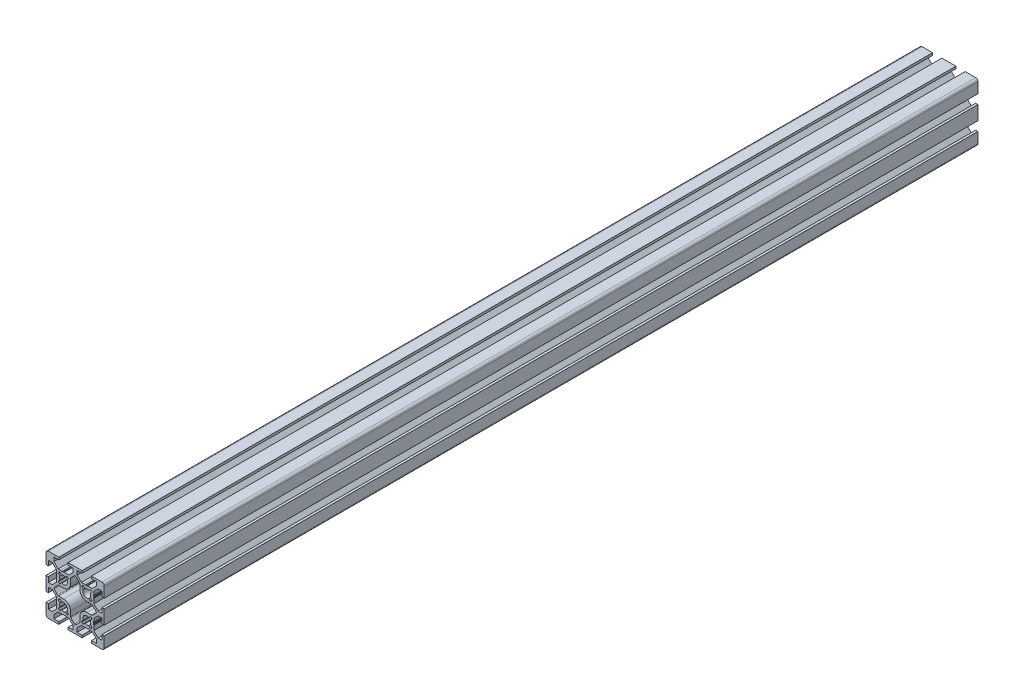
SolidWorks part; units mm, degrees
ref_plane "Front Plane" through (0, 0, 0) normal (0, 0, 1) x (1, 0, 0)
ref_plane "Top Plane" through (0, 0, 0) normal (0, 1, 0) x (1, 0, 0)
ref_plane "Right Plane" through (0, 0, 0) normal (1, 0, 0) x (0, 0, -1)
ref_plane "Plane1" through (0, 0, 0) normal (0, 0, 1) x (1, 0, 0)
sketch "Sketch1" plane through (0, 0, 0) normal (0, 0, 1) x (1, 0, 0)
  line L0 (-25, 23) -> (-25, 14)
  line L1 (-25, 14) -> (-23, 14)
  line L2 (-23, 14) -> (-23, 18.25)
  line L3 (-23, 18.25) -> (-19.6642, 18.25)
  line L4 (-19.6642, 18.25) -> (-16, 14.5858)
  line L5 (-16, 14.5858) -> (-16, 10.6536)
  line L6 (-15.933, 10.4036) -> (-15.7, 10)
  line L7 (-15.7, 10) -> (-15.933, 9.5964)
  line L8 (-15.933, 9.0964) -> (-15.751, 8.7811)
  line L9 (-15.751, 8.7811) -> (-16, 7.5)
  line L10 (-16, 7.5) -> (-16, 5.4142)
  line L11 (-16, 5.4142) -> (-19.6642, 1.75)
  line L12 (-19.6642, 1.75) -> (-23, 1.75)
  line L13 (-23, 1.75) -> (-23, 6)
  line L14 (-23, 6) -> (-25, 6)
  line L15 (-25, 6) -> (-25, -6)
  line L16 (-25, -6) -> (-23, -6)
  line L17 (-23, -6) -> (-23, -1.75)
  line L18 (-23, -1.75) -> (-19.6642, -1.75)
  line L19 (-19.6642, -1.75) -> (-16, -5.4142)
  line L20 (-16, -5.4142) -> (-16, -9.3464)
  line L21 (-15.933, -9.5964) -> (-15.7, -10)
  line L22 (-15.7, -10) -> (-15.933, -10.4036)
  line L23 (-15.933, -10.9036) -> (-15.751, -11.2189)
  line L24 (-15.751, -11.2189) -> (-16, -12.5)
  line L25 (-16, -12.5) -> (-16, -14.5858)
  line L26 (-16, -14.5858) -> (-19.6642, -18.25)
  line L27 (-19.6642, -18.25) -> (-23, -18.25)
  line L28 (-23, -18.25) -> (-23, -14)
  line L29 (-23, -14) -> (-25, -14)
  line L30 (-25, -14) -> (-25, -23)
  line L31 (-23, -25) -> (-14, -25)
  line L32 (-14, -25) -> (-14, -23)
  line L33 (-14, -23) -> (-18.25, -23)
  line L34 (-18.25, -23) -> (-18.25, -19.6642)
  line L35 (-18.25, -19.6642) -> (-14.5858, -16)
  line L36 (-14.5858, -16) -> (-10.6536, -16)
  line L37 (-10.4036, -15.933) -> (-10, -15.7)
  line L38 (-10, -15.7) -> (-9.5964, -15.933)
  line L39 (-9.0964, -15.933) -> (-8.7811, -15.751)
  line L40 (-8.7811, -15.751) -> (-7.5, -16)
  line L41 (-7.5, -16) -> (-5.4142, -16)
  line L42 (-5.4142, -16) -> (-1.75, -19.6642)
  line L43 (-1.75, -19.6642) -> (-1.75, -23)
  line L44 (-1.75, -23) -> (-6, -23)
  line L45 (-6, -23) -> (-6, -25)
  line L46 (-6, -25) -> (6, -25)
  line L47 (6, -25) -> (6, -23)
  line L48 (6, -23) -> (1.75, -23)
  line L49 (1.75, -23) -> (1.75, -19.6642)
  line L50 (1.75, -19.6642) -> (5.4142, -16)
  line L51 (5.4142, -16) -> (9.3464, -16)
  line L52 (9.5964, -15.933) -> (10, -15.7)
  line L53 (10, -15.7) -> (10.4036, -15.933)
  line L54 (10.9036, -15.933) -> (11.2189, -15.751)
  line L55 (11.2189, -15.751) -> (12.5, -16)
  line L56 (12.5, -16) -> (14.5858, -16)
  line L57 (14.5858, -16) -> (18.25, -19.6642)
  line L58 (18.25, -19.6642) -> (18.25, -23)
  line L59 (18.25, -23) -> (14, -23)
  line L60 (14, -23) -> (14, -25)
  line L61 (14, -25) -> (23, -25)
  line L62 (25, -23) -> (25, -14)
  line L63 (25, -14) -> (23, -14)
  line L64 (23, -14) -> (23, -18.25)
  line L65 (23, -18.25) -> (19.6642, -18.25)
  line L66 (19.6642, -18.25) -> (16, -14.5858)
  line L67 (16, -14.5858) -> (16, -10.6536)
  line L68 (15.933, -10.4036) -> (15.7, -10)
  line L69 (15.7, -10) -> (15.933, -9.5964)
  line L70 (15.933, -9.0964) -> (15.751, -8.7811)
  line L71 (15.751, -8.7811) -> (16, -7.5)
  line L72 (16, -7.5) -> (16, -5.4142)
  line L73 (16, -5.4142) -> (19.6642, -1.75)
  line L74 (19.6642, -1.75) -> (23, -1.75)
  line L75 (23, -1.75) -> (23, -6)
  line L76 (23, -6) -> (25, -6)
  line L77 (25, -6) -> (25, 6)
  line L78 (25, 6) -> (23, 6)
  line L79 (23, 6) -> (23, 1.75)
  line L80 (23, 1.75) -> (19.6642, 1.75)
  line L81 (19.6642, 1.75) -> (16, 5.4142)
  line L82 (16, 5.4142) -> (16, 9.3464)
  line L83 (15.933, 9.5964) -> (15.7, 10)
  line L84 (15.7, 10) -> (15.933, 10.4036)
  line L85 (15.933, 10.9036) -> (15.751, 11.2189)
  line L86 (15.751, 11.2189) -> (16, 12.5)
  line L87 (16, 12.5) -> (16, 14.5858)
  line L88 (16, 14.5858) -> (19.6642, 18.25)
  line L89 (19.6642, 18.25) -> (23, 18.25)
  line L90 (23, 18.25) -> (23, 14)
  line L91 (23, 14) -> (25, 14)
  line L92 (25, 14) -> (25, 23)
  line L93 (23, 25) -> (14, 25)
  line L94 (14, 25) -> (14, 23)
  line L95 (14, 23) -> (18.25, 23)
  line L96 (18.25, 23) -> (18.25, 19.6642)
  line L97 (18.25, 19.6642) -> (14.5858, 16)
  line L98 (14.5858, 16) -> (10.6536, 16)
  line L99 (10.4036, 15.933) -> (10, 15.7)
  line L100 (10, 15.7) -> (9.5964, 15.933)
  line L101 (9.0964, 15.933) -> (8.7811, 15.751)
  line L102 (8.7811, 15.751) -> (7.5, 16)
  line L103 (7.5, 16) -> (5.4142, 16)
  line L104 (5.4142, 16) -> (1.75, 19.6642)
  line L105 (1.75, 19.6642) -> (1.75, 23)
  line L106 (1.75, 23) -> (6, 23)
  line L107 (6, 23) -> (6, 25)
  line L108 (6, 25) -> (-6, 25)
  line L109 (-6, 25) -> (-6, 23)
  line L110 (-6, 23) -> (-1.75, 23)
  line L111 (-1.75, 23) -> (-1.75, 19.6642)
  line L112 (-1.75, 19.6642) -> (-5.4142, 16)
  line L113 (-5.4142, 16) -> (-9.3464, 16)
  line L114 (-9.5964, 15.933) -> (-10, 15.7)
  line L115 (-10, 15.7) -> (-10.4036, 15.933)
  line L116 (-10.9036, 15.933) -> (-11.2189, 15.751)
  line L117 (-11.2189, 15.751) -> (-12.5, 16)
  line L118 (-12.5, 16) -> (-14.5858, 16)
  line L119 (-14.5858, 16) -> (-18.25, 19.6642)
  line L120 (-18.25, 19.6642) -> (-18.25, 23)
  line L121 (-18.25, 23) -> (-14, 23)
  line L122 (-14, 23) -> (-14, 25)
  line L123 (-14, 25) -> (-23, 25)
  line L124 (-17.8787, -0.7071) -> (-14.8787, -3.7071)
  line L125 (-14.1716, -4) -> (-10, -4)
  line L126 (-4, -10) -> (-4, -14.1716)
  line L127 (-3.7071, -14.8787) -> (-0.7071, -17.8787)
  line L128 (0.7071, -17.8787) -> (3.7071, -14.8787)
  line L129 (4, -14.1716) -> (4, -10)
  line L130 (10, -4) -> (14.1716, -4)
  line L131 (14.8787, -3.7071) -> (17.8787, -0.7071)
  line L132 (17.8787, 0.7071) -> (14.8787, 3.7071)
  line L133 (14.1716, 4) -> (10, 4)
  line L134 (4, 10) -> (4, 14.1716)
  line L135 (3.7071, 14.8787) -> (0.7071, 17.8787)
  line L136 (-0.7071, 17.8787) -> (-3.7071, 14.8787)
  line L137 (-4, 14.1716) -> (-4, 10)
  line L138 (-10, 4) -> (-14.1716, 4)
  line L139 (-14.8787, 3.7071) -> (-17.8787, 0.7071)
  arc A0 (-16, 10.6536) -> (-15.933, 10.4036) centre (-15.5, 10.6536) ccw
  arc A1 (-15.933, 9.5964) -> (-15.933, 9.0964) centre (-15.5, 9.3464) ccw
  arc A2 (-16, -9.3464) -> (-15.933, -9.5964) centre (-15.5, -9.3464) ccw
  arc A3 (-15.933, -10.4036) -> (-15.933, -10.9036) centre (-15.5, -10.6536) ccw
  arc A4 (-25, -23) -> (-23, -25) centre (-23, -23) ccw
  arc A5 (-10.6536, -16) -> (-10.4036, -15.933) centre (-10.6536, -15.5) ccw
  arc A6 (-9.5964, -15.933) -> (-9.0964, -15.933) centre (-9.3464, -15.5) ccw
  arc A7 (9.3464, -16) -> (9.5964, -15.933) centre (9.3464, -15.5) ccw
  arc A8 (10.4036, -15.933) -> (10.9036, -15.933) centre (10.6536, -15.5) ccw
  arc A9 (23, -25) -> (25, -23) centre (23, -23) ccw
  arc A10 (16, -10.6536) -> (15.933, -10.4036) centre (15.5, -10.6536) ccw
  arc A11 (15.933, -9.5964) -> (15.933, -9.0964) centre (15.5, -9.3464) ccw
  arc A12 (16, 9.3464) -> (15.933, 9.5964) centre (15.5, 9.3464) ccw
  arc A13 (15.933, 10.4036) -> (15.933, 10.9036) centre (15.5, 10.6536) ccw
  arc A14 (25, 23) -> (23, 25) centre (23, 23) ccw
  arc A15 (10.6536, 16) -> (10.4036, 15.933) centre (10.6536, 15.5) ccw
  arc A16 (9.5964, 15.933) -> (9.0964, 15.933) centre (9.3464, 15.5) ccw
  arc A17 (-9.3464, 16) -> (-9.5964, 15.933) centre (-9.3464, 15.5) ccw
  arc A18 (-10.4036, 15.933) -> (-10.9036, 15.933) centre (-10.6536, 15.5) ccw
  arc A19 (-23, 25) -> (-25, 23) centre (-23, 23) ccw
  arc A20 (-17.8787, 0.7071) -> (-17.8787, -0.7071) centre (-17.1716, 0) ccw
  arc A21 (-14.8787, -3.7071) -> (-14.1716, -4) centre (-14.1716, -3) ccw
  arc A22 (-10, -4) -> (-4, -10) centre (-10, -10) cw
  arc A23 (-4, -14.1716) -> (-3.7071, -14.8787) centre (-3, -14.1716) ccw
  arc A24 (-0.7071, -17.8787) -> (0.7071, -17.8787) centre (0, -17.1716) ccw
  arc A25 (3.7071, -14.8787) -> (4, -14.1716) centre (3, -14.1716) ccw
  arc A26 (4, -10) -> (10, -4) centre (10, -10) cw
  arc A27 (14.1716, -4) -> (14.8787, -3.7071) centre (14.1716, -3) ccw
  arc A28 (17.8787, -0.7071) -> (17.8787, 0.7071) centre (17.1716, 0) ccw
  arc A29 (14.8787, 3.7071) -> (14.1716, 4) centre (14.1716, 3) ccw
  arc A30 (10, 4) -> (4, 10) centre (10, 10) cw
  arc A31 (4, 14.1716) -> (3.7071, 14.8787) centre (3, 14.1716) ccw
  arc A32 (0.7071, 17.8787) -> (-0.7071, 17.8787) centre (0, 17.1716) ccw
  arc A33 (-3.7071, 14.8787) -> (-4, 14.1716) centre (-3, 14.1716) ccw
  arc A34 (-4, 10) -> (-10, 4) centre (-10, 10) cw
  arc A35 (-14.1716, 4) -> (-14.8787, 3.7071) centre (-14.1716, 3) ccw
extrude "Boss-Extrude1" add sketch "Sketch1" against normal blind 750
ref_plane "Plane2" through (0, 0, 0) normal (0, 0, 1) x (1, 0, 0)
sketch "Sketch2" plane through (0, 0, 0) normal (0, 0, 1) x (1, 0, 0)
  line L0 (-14.2426, 12.8284) -> (-13.2051, 11.7909)
  line L1 (-13.2051, 8.2091) -> (-14.2426, 7.1716)
  line L2 (-14.2426, 6.4645) -> (-13.5355, 5.7574)
  line L3 (-12.8284, 5.7574) -> (-11.7909, 6.7949)
  line L4 (-6.7949, 11.7909) -> (-5.7574, 12.8284)
  line L5 (-5.7574, 13.5355) -> (-6.4645, 14.2426)
  line L6 (-7.1716, 14.2426) -> (-8.2091, 13.2051)
  line L7 (-11.7909, 13.2051) -> (-12.8284, 14.2426)
  line L8 (-13.5355, 14.2426) -> (-14.2426, 13.5355)
  arc A0 (-14.2426, 13.5355) -> (-14.2426, 12.8284) centre (-13.8891, 13.182) ccw
  arc A1 (-13.2051, 11.7909) -> (-13.1208, 11.3493) centre (-13.4879, 11.508) cw
  arc A2 (-13.1208, 11.3493) -> (-13.1208, 8.6507) centre (-10, 10) ccw
  arc A3 (-13.1208, 8.6507) -> (-13.2051, 8.2091) centre (-13.4879, 8.492) cw
  arc A4 (-14.2426, 7.1716) -> (-14.2426, 6.4645) centre (-13.8891, 6.818) ccw
  arc A5 (-13.5355, 5.7574) -> (-12.8284, 5.7574) centre (-13.182, 6.1109) ccw
  arc A6 (-11.7909, 6.7949) -> (-11.3493, 6.8792) centre (-11.508, 6.5121) cw
  arc A7 (-11.3493, 6.8792) -> (-6.8792, 11.3493) centre (-10, 10) ccw
  arc A8 (-6.8792, 11.3493) -> (-6.7949, 11.7909) centre (-6.5121, 11.508) cw
  arc A9 (-5.7574, 12.8284) -> (-5.7574, 13.5355) centre (-6.1109, 13.182) ccw
  arc A10 (-6.4645, 14.2426) -> (-7.1716, 14.2426) centre (-6.818, 13.8891) ccw
  arc A11 (-8.2091, 13.2051) -> (-8.6507, 13.1208) centre (-8.492, 13.4879) cw
  arc A12 (-8.6507, 13.1208) -> (-11.3493, 13.1208) centre (-10, 10) ccw
  arc A13 (-11.3493, 13.1208) -> (-11.7909, 13.2051) centre (-11.508, 13.4879) cw
  arc A14 (-12.8284, 14.2426) -> (-13.5355, 14.2426) centre (-13.182, 13.8891) ccw
extrude "Cut-Extrude1" cut sketch "Sketch2" against normal through all
ref_plane "Plane3" through (0, 0, 0) normal (0, 0, 1) x (1, 0, 0)
sketch "Sketch3" plane through (0, 0, 0) normal (0, 0, 1) x (1, 0, 0)
  line L0 (-12.8284, -14.2426) -> (-11.7909, -13.2051)
  line L1 (-8.2091, -13.2051) -> (-7.1716, -14.2426)
  line L2 (-6.4645, -14.2426) -> (-5.7574, -13.5355)
  line L3 (-5.7574, -12.8284) -> (-6.7949, -11.7909)
  line L4 (-11.7909, -6.7949) -> (-12.8284, -5.7574)
  line L5 (-13.5355, -5.7574) -> (-14.2426, -6.4645)
  line L6 (-14.2426, -7.1716) -> (-13.2051, -8.2091)
  line L7 (-13.2051, -11.7909) -> (-14.2426, -12.8284)
  line L8 (-14.2426, -13.5355) -> (-13.5355, -14.2426)
  arc A0 (-13.5355, -14.2426) -> (-12.8284, -14.2426) centre (-13.182, -13.8891) ccw
  arc A1 (-11.7909, -13.2051) -> (-11.3493, -13.1208) centre (-11.508, -13.4879) cw
  arc A2 (-11.3493, -13.1208) -> (-8.6507, -13.1208) centre (-10, -10) ccw
  arc A3 (-8.6507, -13.1208) -> (-8.2091, -13.2051) centre (-8.492, -13.4879) cw
  arc A4 (-7.1716, -14.2426) -> (-6.4645, -14.2426) centre (-6.818, -13.8891) ccw
  arc A5 (-5.7574, -13.5355) -> (-5.7574, -12.8284) centre (-6.1109, -13.182) ccw
  arc A6 (-6.7949, -11.7909) -> (-6.8792, -11.3493) centre (-6.5121, -11.508) cw
  arc A7 (-6.8792, -11.3493) -> (-11.3493, -6.8792) centre (-10, -10) ccw
  arc A8 (-11.3493, -6.8792) -> (-11.7909, -6.7949) centre (-11.508, -6.5121) cw
  arc A9 (-12.8284, -5.7574) -> (-13.5355, -5.7574) centre (-13.182, -6.1109) ccw
  arc A10 (-14.2426, -6.4645) -> (-14.2426, -7.1716) centre (-13.8891, -6.818) ccw
  arc A11 (-13.2051, -8.2091) -> (-13.1208, -8.6507) centre (-13.4879, -8.492) cw
  arc A12 (-13.1208, -8.6507) -> (-13.1208, -11.3493) centre (-10, -10) ccw
  arc A13 (-13.1208, -11.3493) -> (-13.2051, -11.7909) centre (-13.4879, -11.508) cw
  arc A14 (-14.2426, -12.8284) -> (-14.2426, -13.5355) centre (-13.8891, -13.182) ccw
extrude "Cut-Extrude2" cut sketch "Sketch3" against normal through all
ref_plane "Plane4" through (0, 0, 0) normal (0, 0, 1) x (1, 0, 0)
sketch "Sketch4" plane through (0, 0, 0) normal (0, 0, 1) x (1, 0, 0)
  line L0 (14.2426, -12.8284) -> (13.2051, -11.7909)
  line L1 (13.2051, -8.2091) -> (14.2426, -7.1716)
  line L2 (14.2426, -6.4645) -> (13.5355, -5.7574)
  line L3 (12.8284, -5.7574) -> (11.7909, -6.7949)
  line L4 (6.7949, -11.7909) -> (5.7574, -12.8284)
  line L5 (5.7574, -13.5355) -> (6.4645, -14.2426)
  line L6 (7.1716, -14.2426) -> (8.2091, -13.2051)
  line L7 (11.7909, -13.2051) -> (12.8284, -14.2426)
  line L8 (13.5355, -14.2426) -> (14.2426, -13.5355)
  arc A0 (14.2426, -13.5355) -> (14.2426, -12.8284) centre (13.8891, -13.182) ccw
  arc A1 (13.2051, -11.7909) -> (13.1208, -11.3493) centre (13.4879, -11.508) cw
  arc A2 (13.1208, -11.3493) -> (13.1208, -8.6507) centre (10, -10) ccw
  arc A3 (13.1208, -8.6507) -> (13.2051, -8.2091) centre (13.4879, -8.492) cw
  arc A4 (14.2426, -7.1716) -> (14.2426, -6.4645) centre (13.8891, -6.818) ccw
  arc A5 (13.5355, -5.7574) -> (12.8284, -5.7574) centre (13.182, -6.1109) ccw
  arc A6 (11.7909, -6.7949) -> (11.3493, -6.8792) centre (11.508, -6.5121) cw
  arc A7 (11.3493, -6.8792) -> (6.8792, -11.3493) centre (10, -10) ccw
  arc A8 (6.8792, -11.3493) -> (6.7949, -11.7909) centre (6.5121, -11.508) cw
  arc A9 (5.7574, -12.8284) -> (5.7574, -13.5355) centre (6.1109, -13.182) ccw
  arc A10 (6.4645, -14.2426) -> (7.1716, -14.2426) centre (6.818, -13.8891) ccw
  arc A11 (8.2091, -13.2051) -> (8.6507, -13.1208) centre (8.492, -13.4879) cw
  arc A12 (8.6507, -13.1208) -> (11.3493, -13.1208) centre (10, -10) ccw
  arc A13 (11.3493, -13.1208) -> (11.7909, -13.2051) centre (11.508, -13.4879) cw
  arc A14 (12.8284, -14.2426) -> (13.5355, -14.2426) centre (13.182, -13.8891) ccw
extrude "Cut-Extrude3" cut sketch "Sketch4" against normal through all
ref_plane "Plane5" through (0, 0, 0) normal (0, 0, 1) x (1, 0, 0)
sketch "Sketch5" plane through (0, 0, 0) normal (0, 0, 1) x (1, 0, 0)
  line L0 (12.8284, 14.2426) -> (11.7909, 13.2051)
  line L1 (8.2091, 13.2051) -> (7.1716, 14.2426)
  line L2 (6.4645, 14.2426) -> (5.7574, 13.5355)
  line L3 (5.7574, 12.8284) -> (6.7949, 11.7909)
  line L4 (11.7909, 6.7949) -> (12.8284, 5.7574)
  line L5 (13.5355, 5.7574) -> (14.2426, 6.4645)
  line L6 (14.2426, 7.1716) -> (13.2051, 8.2091)
  line L7 (13.2051, 11.7909) -> (14.2426, 12.8284)
  line L8 (14.2426, 13.5355) -> (13.5355, 14.2426)
  arc A0 (13.5355, 14.2426) -> (12.8284, 14.2426) centre (13.182, 13.8891) ccw
  arc A1 (11.7909, 13.2051) -> (11.3493, 13.1208) centre (11.508, 13.4879) cw
  arc A2 (11.3493, 13.1208) -> (8.6507, 13.1208) centre (10, 10) ccw
  arc A3 (8.6507, 13.1208) -> (8.2091, 13.2051) centre (8.492, 13.4879) cw
  arc A4 (7.1716, 14.2426) -> (6.4645, 14.2426) centre (6.818, 13.8891) ccw
  arc A5 (5.7574, 13.5355) -> (5.7574, 12.8284) centre (6.1109, 13.182) ccw
  arc A6 (6.7949, 11.7909) -> (6.8792, 11.3493) centre (6.5121, 11.508) cw
  arc A7 (6.8792, 11.3493) -> (11.3493, 6.8792) centre (10, 10) ccw
  arc A8 (11.3493, 6.8792) -> (11.7909, 6.7949) centre (11.508, 6.5121) cw
  arc A9 (12.8284, 5.7574) -> (13.5355, 5.7574) centre (13.182, 6.1109) ccw
  arc A10 (14.2426, 6.4645) -> (14.2426, 7.1716) centre (13.8891, 6.818) ccw
  arc A11 (13.2051, 8.2091) -> (13.1208, 8.6507) centre (13.4879, 8.492) cw
  arc A12 (13.1208, 8.6507) -> (13.1208, 11.3493) centre (10, 10) ccw
  arc A13 (13.1208, 11.3493) -> (13.2051, 11.7909) centre (13.4879, 11.508) cw
  arc A14 (14.2426, 12.8284) -> (14.2426, 13.5355) centre (13.8891, 13.182) ccw
extrude "Cut-Extrude4" cut sketch "Sketch5" against normal through all
